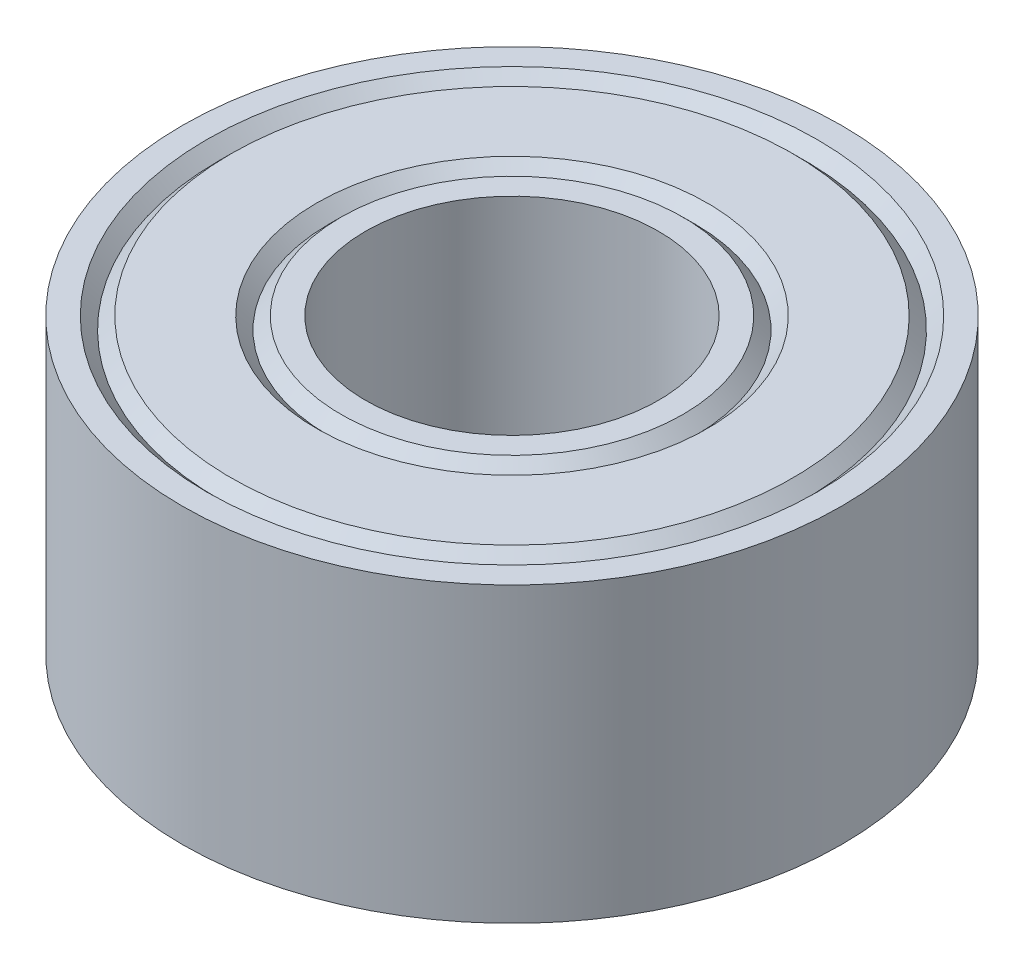
SolidWorks part; units mm, degrees
ref_plane "Front Plane" through (0, 0, 0) normal (0, 0, 1) x (1, 0, 0)
ref_plane "Top Plane" through (0, 0, 0) normal (0, 1, 0) x (1, 0, 0)
ref_plane "Right Plane" through (0, 0, 0) normal (1, 0, 0) x (0, 0, -1)
sketch "Sketch1" plane through (0, 0, 0) normal (0, 0, 1) x (1, 0, 0)
  line L0 (0, 2) -> (0, -2) construction
  line L1 (-2, 2) -> (-2.3333, 2)
  line L2 (-2, 2) -> (-2, -2)
  line L3 (-2, -2) -> (-2.3333, -2)
  line L4 (-4.5, 2) -> (-4.5, -2)
  line L5 (-4.1667, 2) -> (-4, 1.8333)
  line L6 (-4, 1.8333) -> (-3.8333, 2)
  line L7 (-2.6667, 2) -> (-2.5, 1.8333)
  line L8 (-2.5, 1.8333) -> (-2.3333, 2)
  line L9 (-4.1667, -2) -> (-4, -1.8333)
  line L10 (-4, -1.8333) -> (-3.8333, -2)
  line L11 (-2.6667, -2) -> (-2.5, -1.8333)
  line L12 (-2.5, -1.8333) -> (-2.3333, -2)
  line L13 (-2.6667, -2) -> (-3.8333, -2)
  line L14 (-4.1667, -2) -> (-4.5, -2)
  line L15 (-4.1667, 2) -> (-4.5, 2)
  line L16 (-2.6667, 2) -> (-3.8333, 2)
  line L17 (-4, 1.8333) -> (-2.5, 1.8333) construction
  line L18 (-4, 1.8333) -> (-4, -1.8333) construction
  line L19 (-2.5, -1.8333) -> (-4, -1.8333) construction
  line L20 (-2.5, 1.8333) -> (-2.5, -1.8333) construction
  line L21 (-4, 0) -> (-3.5, 0) construction
  line L22 (-2.3333, 2) -> (-2.6667, 2) construction
  line L23 (-3.5, 0) -> (-3, 0) construction
  line L24 (-4, 0) -> (-4.5, 0) construction
  line L25 (-3, 0) -> (-2.5, 0) construction
  line L26 (-2.5, 0) -> (-2, 0) construction
  dimension "D1" = 4
  dimension "D2" = 4
  dimension "D3" = 9
revolve "Revolve1" add sketch "Sketch1" angle 360 about L0
